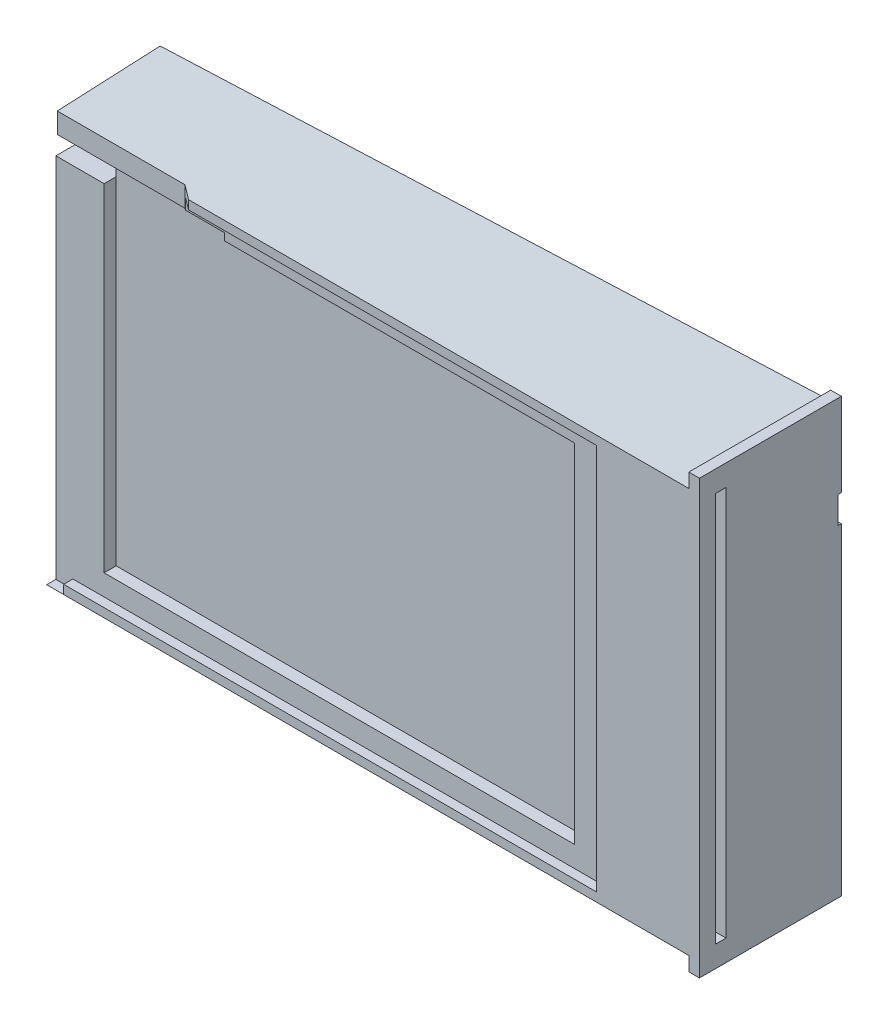
SolidWorks part; units mm, degrees
ref_plane "Front Plane" through (0, 0, 0) normal (0, 0, 1) x (1, 0, 0)
ref_plane "Top Plane" through (0, 0, 0) normal (0, 1, 0) x (1, 0, 0)
ref_plane "Right Plane" through (0, 0, 0) normal (1, 0, 0) x (0, 0, -1)
sketch "Sketch1" plane through (0, 0, 0) normal (0, 0, 1) x (1, 0, 0)
  line L1 (0, 0) -> (92, 0)
  line L2 (0, 0) -> (0, 61)
  line L3 (0, 61) -> (92, 61)
  line L4 (92, 0) -> (92, 61)
  dimension "D1" = 61
  dimension "D2" = 92
ref_plane "Plane1" through (92, 0, 0) normal (1, 0, 0) x (0, 0, -1)
sketch "Sketch2" plane through (92, 0, 0) normal (1, 0, 0) x (0, 0, -1)
  line L1 (0, 61) -> (20, 61.75)
  line L2 (0, 61) -> (0, 4)
  line L3 (0, 4) -> (20, 3.25)
  line L4 (20, 61.75) -> (20, 3.25)
  dimension "D1" = 20
  dimension "D2" = 57
  dimension "D3" = 58.5
ref_plane "Plane2" through (0, 0, 0) normal (1, 0, 0) x (0, 0, -1)
sketch "Sketch3" plane through (0, 0, 0) normal (1, 0, 0) x (0, 0, -1)
  line L1 (0, 61) -> (16, 61.75)
  line L2 (0, 61) -> (0, 4)
  line L3 (0, 4) -> (16, 3.25)
  line L4 (16, 61.75) -> (16, 3.25)
  dimension "D1" = 16
  dimension "D2" = 58.5
  dimension "D3" = 57
ref_plane "Plane3" through (0, 61, 0) normal (0, 1, 0) x (1, 0, 0)
loft "body" add profiles "Sketch3", "Sketch2"
sketch "Sketch5" plane through (0, 61, 0) normal (0, 1, 0) x (1, 0, 0)
  line L0 (0, 1.5) -> (18, 1.5)
  line L1 (0, -33.55) -> (0, 33.55) construction
  line L2 (18, 1.5) -> (20, 0)
  line L3 (0, 0) -> (92, 0) construction
  line L4 (0, 1.5) -> (0, 0)
  line L5 (0, 0) -> (20, 0)
  dimension "D1" = 1.5
  dimension "D2" = 20
  dimension "D3" = 2
sketch "Sketch6" plane through (0, 0, 0) normal (0, 0, 1) x (1, 0, 0)
  line L0 (23.8, 57.2) -> (23.8, 58.2)
  line L1 (6.8, 8.2) -> (73.1, 8.2)
  line L2 (6.8, 8.2) -> (6.8, 57.2)
  line L3 (6.8, 57.2) -> (73.1, 57.2)
  line L4 (73.1, 8.2) -> (73.1, 57.2)
  line L5 (6.8, 8.2) -> (73.1, 57.2) construction
  line L6 (6.8, 57.2) -> (73.1, 8.2) construction
  line L7 (23.8, 58.2) -> (6.8, 58.2)
  line L9 (0, 61) -> (92, 61) construction
  line L10 (0, 0) -> (0, 61) construction
  line L11 (6.8, 57.2) -> (6.8, 58.2)
  line L12 (6.8, 58.2) -> (6.8, 57.2)
  point P0 (39.95, 32.7)
  dimension "D1" = 66.3
  dimension "D2" = 49
  dimension "D3" = 1
  dimension "D4" = 17
  dimension "D5" = 3.8
  dimension "D6" = 6.8
extrude "film plane" cut sketch "Sketch6" against normal blind 3 contours L11 L3 L0 L7 | L1 L4 L3 L2
sketch "Sketch7" plane through (0, 0, 0) normal (0, 0, 1) x (1, 0, 0)
  line L0 (0, 0) -> (0, 61) construction
  line L1 (77.5, 59.75) -> (0, 59.75)
  line L2 (77.5, 59.75) -> (77.5, 5.25)
  line L3 (77.5, 5.25) -> (0, 5.25)
  line L4 (0, 59.75) -> (0, 5.25)
  line L5 (92, 0) -> (92, 61) construction
  line L6 (77.5, 5.25) -> (77.5, 4) construction
  line L7 (0, 4) -> (92, 4) construction
  line L8 (77.5, 59.75) -> (77.5, 61) construction
  line L9 (0, 61) -> (92, 61) construction
  line L10 (2.4, 5.25) -> (2.4, 4)
  line L11 (2.4, 4) -> (0, 4)
  line L12 (0, 4) -> (0, 5.25)
  dimension "D1" = 54.5
  dimension "D2" = 14.5
  dimension "D3" = 2.4
extrude "Cut-Extrude2" cut sketch "Sketch7" against normal blind 1.3
sketch "notch" plane through (0, 0, -1.3) normal (0, 0, 1) x (1, 0, 0)
  line L0 (6.8, 58.2) -> (0, 58.2)
  line L1 (0, 59.75) -> (0, 4) construction
  line L2 (0, 58.2) -> (0, 55.7)
  line L3 (0, 55.7) -> (6.8, 55.7)
  line L4 (6.8, 58.2) -> (6.8, 8.2) construction
  line L5 (6.8, 55.7) -> (6.8, 58.2)
  dimension "D1" = 2.5
extrude "notch-cut" cut sketch "notch" against normal blind 4.1
sketch "Sketch10" plane through (-0.6943, 0, -15.9698) normal (-0.0434, 0, -0.9991) x (-0.9991, 0, 0.0434)
  line L0 (-92.7819, 51.25) -> (-86.4841, 51.25)
  line L1 (-92.7819, 3.25) -> (-92.7819, 61.75) construction
  line L2 (-86.4841, 51.25) -> (-86.4841, 47.45)
  line L3 (-86.4841, 47.45) -> (-92.7819, 47.45)
  line L4 (-92.7819, 47.45) -> (-92.7819, 51.25)
  line L6 (-92.7819, 61.75) -> (-0.695, 61.75) construction
  dimension "D1" = 10.5
  dimension "D2" = 3.8
extrude "Cut-Extrude4" cut sketch "Sketch10" against normal blind 0.5
sketch "Sketch11" plane through (-0.6943, 0, -15.9698) normal (-0.0434, 0, -0.9991) x (-0.9991, 0, 0.0434)
  line L0 (-92.7819, 3.25) -> (-92.7819, 47.45) construction
  line L1 (-72.5, 14.5) -> (-64, 14.5)
  line L2 (-75, 17) -> (-75, 48)
  line L3 (-72.5, 50.5) -> (-64, 50.5)
  line L4 (-61.5, 17) -> (-61.5, 48)
  line L5 (-24.5, 14.5) -> (-16, 14.5)
  line L6 (-27, 17) -> (-27, 48)
  line L7 (-24.5, 50.5) -> (-16, 50.5)
  line L8 (-13.5, 17) -> (-13.5, 48)
  line L11 (-0.695, 32.5) -> (-92.7819, 32.5) construction
  line L12 (-0.695, 3.25) -> (-0.695, 61.75) construction
  line L13 (0, 0) -> (0, 61) construction
  arc A0 (-24.5, 14.5) -> (-27, 17) centre (-24.5, 17) cw
  arc A1 (-16, 14.5) -> (-13.5, 17) centre (-16, 17) ccw
  arc A2 (-16, 50.5) -> (-13.5, 48) centre (-16, 48) cw
  arc A3 (-27, 48) -> (-24.5, 50.5) centre (-24.5, 48) cw
  arc A4 (-75, 48) -> (-72.5, 50.5) centre (-72.5, 48) cw
  arc A5 (-64, 50.5) -> (-61.5, 48) centre (-64, 48) cw
  arc A6 (-64, 14.5) -> (-61.5, 17) centre (-64, 17) ccw
  arc A7 (-72.5, 14.5) -> (-75, 17) centre (-72.5, 17) cw
  point P10 (-13.5, 32.5)
  point P27 (-75, 50.5)
  point P34 (-75, 14.5)
  dimension "D6" = 2.5
  dimension "D1" = 36
  dimension "D3" = 34.5
  dimension "D4" = 13.5
  dimension "D2" = 13.5
  dimension "D5" = 13.5
extrude "Cut-Extrude5" cut sketch "Sketch11" against normal blind 1.5
extrude "Cut-Extrude6" cut sketch "Sketch5" against normal blind 5 and the other way through all
sketch "草图1" plane through (92, 0, 0) normal (1, 0, 0) x (0, 0, -1)
  line L0 (3, 60) -> (3, 5)
  line L1 (0, 61) -> (0, 4) construction
  point P5 (0, 32.5)
  point P6 (3, 32.5)
  dimension "D1" = 3
  dimension "D2" = 55
extrude "outlet" cut sketch "草图1" against normal blind 2 thin thin type mid plane wall 1.5
ref_plane "基准面1" through (92, 61.75, -20) normal (0, 1, 0) x (1, 0, 0)
ref_plane "基准面2" through (92, 61.75, -20) normal (0, -0.0375, 0.9993) x (1, 0, 0)
ref_plane "基准面3" through (92, 61, 0) normal (0, -0.0375, 0.9993) x (1, 0, 0)
sketch "草图6" plane through (0, 0, 0) normal (0, 0, 1) x (1, 0, 0)
  line L0 (92, 61) -> (92, 4) construction
  line L1 (92, 61) -> (90.5, 61)
  line L2 (92, 61) -> (92, 63)
  line L3 (92, 63) -> (90.5, 63)
  line L4 (90.5, 61) -> (90.5, 63)
  line L5 (2.4, 4) -> (92, 4) construction
  line L6 (92, 4) -> (90.5, 4)
  line L7 (92, 4) -> (92, 2)
  line L8 (92, 2) -> (90.5, 2)
  line L9 (90.5, 4) -> (90.5, 2)
  line L10 (0, 61) -> (92, 61) construction
  dimension "D1" = 1.5
  dimension "D2" = 2
extrude "凸台-拉伸1" add sketch "草图6" against normal up to vertex (20 mm away) up to point (92, 61.75, -20)
equation "\"D5@Sketch11\"=\"D2@Sketch11\""
